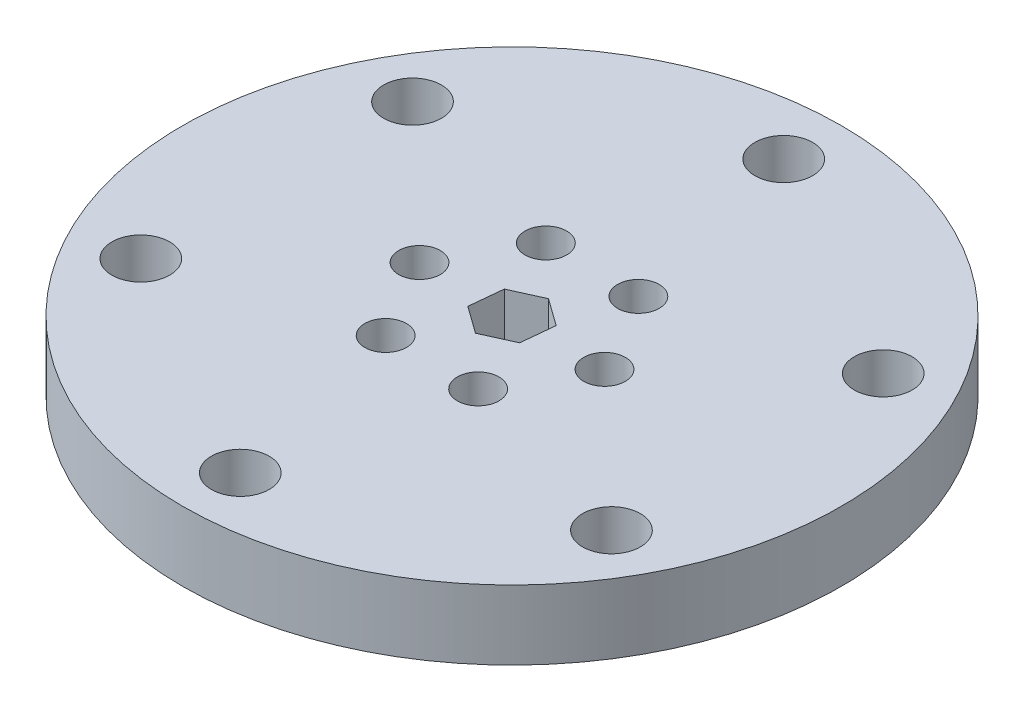
SolidWorks part; units mm, degrees
ref_plane "Front" through (0, 0, 0) normal (0, 0, 1) x (1, 0, 0)
ref_plane "Top" through (0, 0, 0) normal (0, 1, 0) x (1, 0, 0)
ref_plane "Right" through (0, 0, 0) normal (1, 0, 0) x (0, 0, -1)
sketch "Sketch1" plane through (0, 0, 0) normal (0, 1, 0) x (1, 0, 0)
  circle A0 centre (0, 0) radius 28.5
  circle A1 centre (0, 0) radius 23.5
  circle A2 centre (0, 23.5) radius 2.5
  circle A3 centre (20.3516, 11.75) radius 2.5
  circle A4 centre (20.3516, -11.75) radius 2.5
  circle A5 centre (0, -23.5) radius 2.5
  circle A6 centre (-20.3516, -11.75) radius 2.5
  circle A7 centre (-20.3516, 11.75) radius 2.5
  point P18 (0, 0)
  dimension "D1" = 57
  dimension "D2" = 47
  dimension "D3" = 5
  dimension "D4" = 6
extrude "Boss-Extrude1" add sketch "Sketch1" along normal blind 6 contours A0 A7 A1 A2 A3 A4 A5 A6 | A7 A1 A6 A5 A4 A3 A2
sketch "Sketch2" plane through (0, 6, 0) normal (0, 1, 0) x (1, 0, 0)
  line L1 (-0.2845, -2.8727) -> (2.3456, -1.6828)
  line L2 (2.3456, -1.6828) -> (2.6301, 1.1899)
  line L3 (2.6301, 1.1899) -> (0.2845, 2.8727)
  line L4 (0.2845, 2.8727) -> (-2.3456, 1.6828)
  line L5 (-2.3456, 1.6828) -> (-2.6301, -1.1899)
  line L6 (-2.6301, -1.1899) -> (-0.2845, -2.8727)
  circle A0 centre (0, 0) radius 2.5 construction
  dimension "D1" = 5
extrude "Cut-Extrude1" cut sketch "Sketch2" against normal blind 8
sketch "Sketch3" plane through (0, 6, 0) normal (0, 1, 0) x (1, 0, 0)
  circle A0 centre (0, 0) radius 8
  circle A1 centre (8, 0) radius 1.8
  circle A2 centre (4, -6.9282) radius 1.8
  circle A3 centre (-4, -6.9282) radius 1.8
  circle A4 centre (-8, 0) radius 1.8
  circle A5 centre (-4, 6.9282) radius 1.8
  circle A6 centre (4, 6.9282) radius 1.8
  point P17 (0, 0)
  dimension "D1" = 16
  dimension "D2" = 6
extrude "Cut-Extrude2" cut sketch "Sketch3" against normal blind 10.54 contours A0 A5 | A0 A5 | A0 A4 | A0 A4 | A0 A3 | A0 A3 | A0 A2 | A0 A2 | A0 A1 | A0 A1 | A0 A6 | A0 A6
